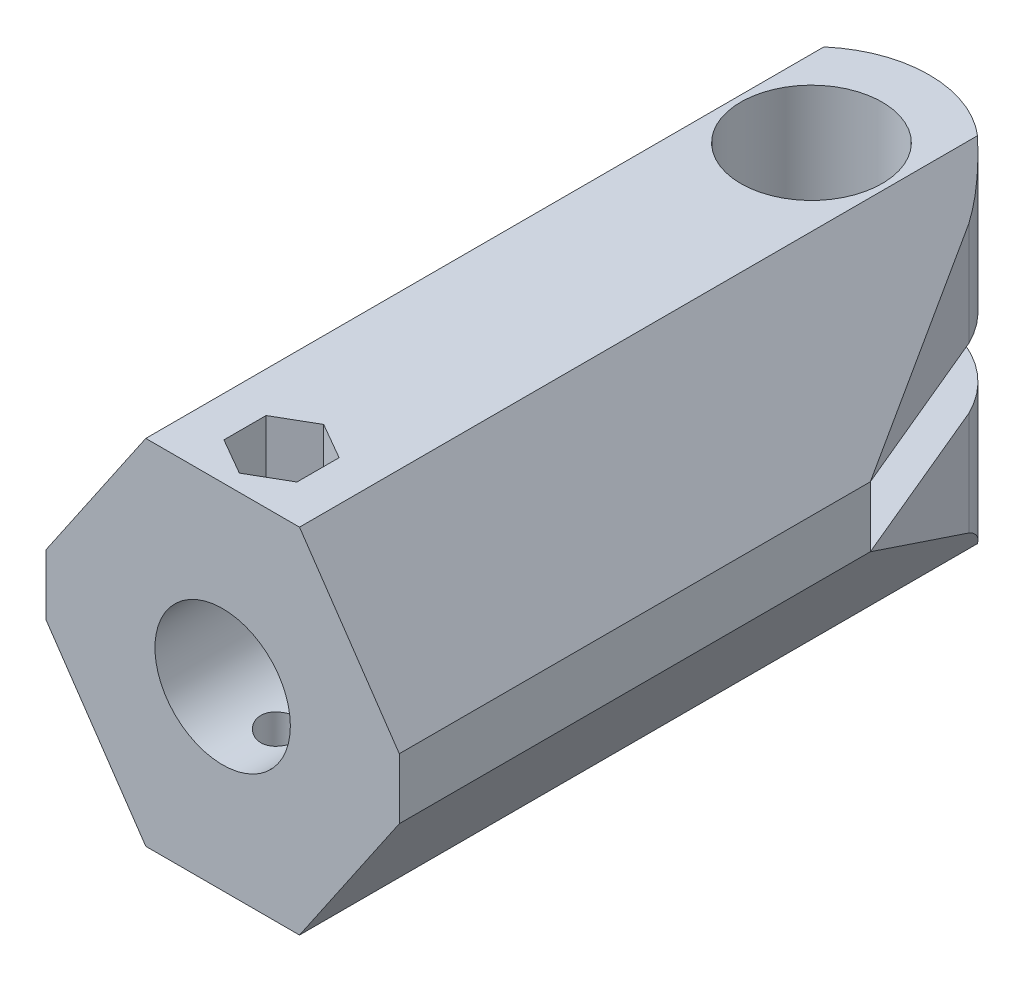
SolidWorks part; units mm, degrees
ref_plane "Front Plane" through (0, 0, 0) normal (0, 0, 1) x (1, 0, 0)
ref_plane "Top Plane" through (0, 0, 0) normal (0, 1, 0) x (1, 0, 0)
ref_plane "Right Plane" through (0, 0, 0) normal (1, 0, 0) x (0, 0, -1)
sketch "Sketch3" plane through (0, 0, 0) normal (0, 0, 1) x (1, 0, 0)
  line L1 (0, 0) -> (30, 0)
  line L2 (0, 0) -> (0, 30)
  line L3 (0, 30) -> (30, 30)
  line L4 (30, 0) -> (30, 30)
  dimension "D1" = 30
  dimension "D2" = 30
extrude "Boss-Extrude1" add sketch "Sketch3" along normal blind 40
sketch "Sketch4" plane through (0, 0, 40) normal (0, 0, 1) x (1, 0, 0)
  line L0 (0, 30) -> (30, 0)
  circle A0 centre (15, 15) radius 5.75
  dimension "D1" = 11.5
extrude "Cut-Extrude1" cut sketch "Sketch4" against normal blind 10 contours L0 A0 | L0 A0
sketch "Sketch5" plane through (0, 0, 0) normal (0, -1, 0) x (1, 0, 0)
  line L0 (15, 40) -> (15, 35)
  line L1 (0, 40) -> (30, 40) construction
  line L3 (15, 38.58) -> (11.8996, 36.79)
  line L4 (11.8996, 36.79) -> (11.8996, 33.21)
  line L5 (11.8996, 33.21) -> (15, 31.42)
  line L6 (15, 31.42) -> (18.1004, 33.21)
  line L7 (18.1004, 33.21) -> (18.1004, 36.79)
  line L8 (18.1004, 36.79) -> (15, 38.58)
  circle A0 centre (15, 35) radius 3.1004 construction
  circle A1 centre (15, 35) radius 1.75
  dimension "D3" = 3.5
  dimension "D1" = 5
  dimension "D2" = 3.58
extrude "Cut-Extrude2" cut sketch "Sketch5" against normal blind 5
ref_plane "Plane1" through (0, 15, 0) normal (0, -1, 0) x (-1, 0, 0)
mirror "Mirror1" about plane through (0, 15, 0) normal (0, -1, 0) of "Cut-Extrude2"
sketch "Sketch6" plane through (0, 25, 0) normal (0, 1, 0) x (1, 0, 0)
  line L0 (15, -38.58) -> (15, -31.42)
  circle A0 centre (15, -35) radius 1.75
  dimension "D1" = 3.5
extrude "Cut-Extrude3" cut sketch "Sketch6" against normal blind 28 contours L0 A0 | L0 A0
sketch "Sketch8" plane through (0, 0, 0) normal (0, 0, -1) x (-1, 0, 0)
  line L0 (-30, 17.573) -> (-21.5266, 30)
  line L1 (-30, 0) -> (-30, 30) construction
  line L2 (-30, 30) -> (0, 30) construction
extrude "Cut-Extrude4" cut sketch "Sketch8" against normal blind 40 and the other way through all
ref_plane "Plane2" through (15, 0, 0) normal (-1, 0, 0) x (0, 0, 1)
mirror "Mirror4" about plane through (15, 0, 0) normal (-1, 0, 0) of "Cut-Extrude4"
mirror "Mirror5" about plane through (0, 15, 0) normal (0, -1, 0) of "Mirror4", "Cut-Extrude4"
sketch "Sketch9" plane through (0, 0, 0) normal (0, 1, 0) x (1, 0, 0)
  line L0 (15, 2.8303) -> (15, -2.8303) construction
  line L1 (21.5266, 0) -> (8.4734, 0) construction
  line L2 (0, 0) -> (5.7692, 13.8462)
  line L3 (30, 0) -> (24.0022, 14.3544)
  line L4 (0, 0) -> (30, 0)
  arc A0 (24.424, 13.3448) -> (5.7692, 13.8462) centre (15, 10) ccw
  circle A1 centre (15, 10) radius 6
  dimension "D1" = 20
  dimension "D2" = 12
extrude "Boss-Extrude2" add sketch "Sketch9" along normal blind 30 contours L3 A0 L2 L4 A1
sketch "Sketch10" plane through (0, 0, 0) normal (0, 0, 1) x (1, 0, 0)
  line L0 (0, 17.573) -> (8.4734, 30)
  line L1 (8.4734, 30) -> (0, 30)
  line L2 (0, 30) -> (0, 17.573)
  line L3 (8.4734, 0) -> (0, 0)
  line L4 (0, 0) -> (0, 12.427)
  line L5 (0, 12.427) -> (8.4734, 0)
  line L6 (21.5266, 0) -> (30, 12.427)
  line L7 (30, 12.427) -> (30, 0)
  line L8 (30, 0) -> (21.5266, 0)
  line L9 (30, 17.573) -> (21.5266, 30)
  line L10 (21.5266, 30) -> (30, 30)
  line L11 (30, 30) -> (30, 17.573)
extrude "Cut-Extrude5" cut sketch "Sketch10" against normal blind 30
sketch "Sketch11" plane through (30, 0, 0) normal (1, 0, 0) x (0, 0, -1)
  line L1 (0, 12.427) -> (21.3291, 12.427)
  line L2 (0, 12.427) -> (0, 17.573)
  line L3 (0, 17.573) -> (21.3291, 17.573)
  line L4 (21.3291, 12.427) -> (21.3291, 17.573)
extrude "Cut-Extrude6" cut sketch "Sketch11" against normal blind 30
